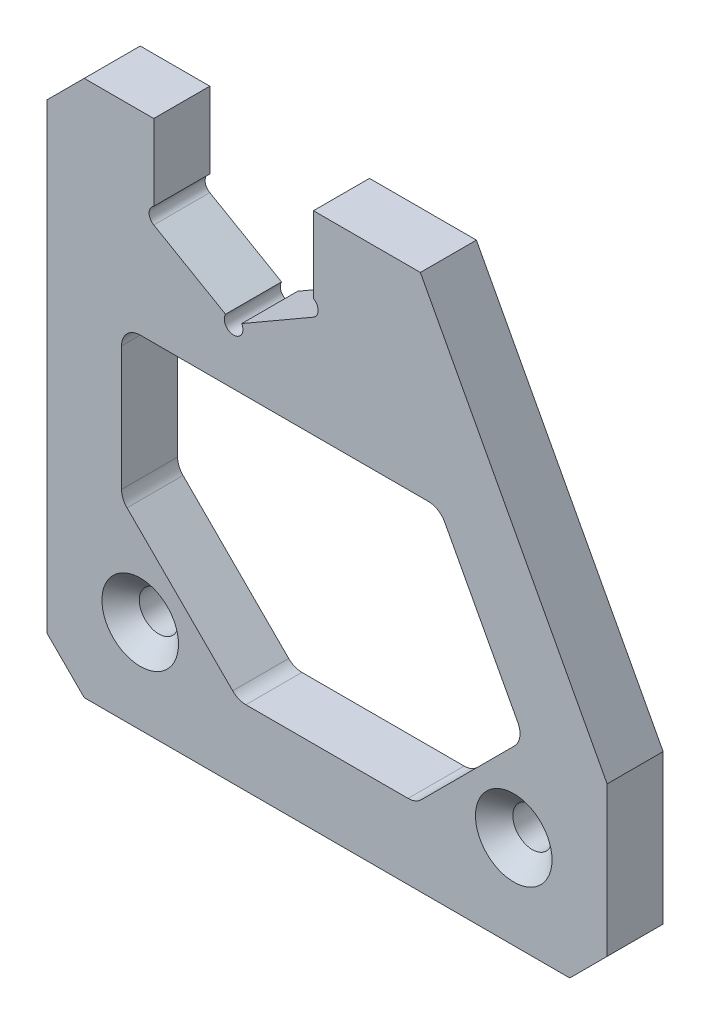
SolidWorks part; units mm, degrees
ref_plane "前视基准面" through (0, 0, 0) normal (0, 0, 1) x (1, 0, 0)
ref_plane "上视基准面" through (0, 0, 0) normal (0, 1, 0) x (1, 0, 0)
ref_plane "右视基准面" through (0, 0, 0) normal (1, 0, 0) x (0, 0, -1)
sketch "草图1" plane through (0, 0, 0) normal (0, 0, 1) x (1, 0, 0)
  line L0 (-20, 4.9363) -> (-20, -52.5)
  line L1 (0, -9.8727) -> (8.55, -4.9363)
  line L2 (8.55, -4.9363) -> (8.55, 4.9363)
  line L3 (8.55, 4.9363) -> (0, 9.8727) construction
  line L4 (0, 9.8727) -> (-8.55, 4.9363) construction
  line L5 (-8.55, 4.9363) -> (-8.55, -4.9363)
  line L6 (-8.55, -4.9363) -> (0, -9.8727)
  line L7 (-20, -52.5) -> (40, -52.5)
  line L8 (-10, -42.5) -> (30, -42.5) construction
  line L11 (40, -32.5) -> (40, -52.5)
  line L13 (20, 4.9363) -> (40, -32.5)
  line L14 (-8.55, 4.9363) -> (-20, 4.9363)
  line L15 (8.55, 4.9363) -> (20, 4.9363)
  circle A0 centre (0, 0) radius 8.55 construction
  circle A1 centre (-10, -42.5) radius 2.1
  circle A2 centre (30, -42.5) radius 2.1
  dimension "D1" = 17.1
  dimension "D4" = 10
  dimension "D6" = 4.2
  dimension "D2" = 20
  dimension "D3" = 52.5
  dimension "D5" = 10
  dimension "D7" = 40
  dimension "D8" = 20
  dimension "D9" = 10
extrude "凸台-拉伸1" add sketch "草图1" along normal mid plane 6
chamfer "倒角1" distance 4 angle 45 3 edges at (40, -52.5, 0) (-20, -52.5, 0) (-20, 4.9363, 0)
sketch "草图2" plane through (0, 0, 3) normal (0, 0, 1) x (1, 0, 0)
  line L0 (0, -9.8727) -> (-8.55, -4.9363) construction
  line L3 (8.55, -4.9363) -> (0, -9.8727) construction
  circle A0 centre (-8.05, -4.0703) radius 1
  circle A1 centre (8.05, -4.0703) radius 1
  circle A2 centre (0, -9.8727) radius 1
  dimension "D1" = 2
extrude "切除-拉伸1" cut sketch "草图2" against normal through all
sketch "草图3" plane through (0, 0, 3) normal (0, 0, 1) x (1, 0, 0)
  line L0 (-12, -15.8727) -> (-12, -32.0147)
  line L1 (-12, -15.8727) -> (22.0469, -15.8727)
  line L2 (22.0469, -15.8727) -> (31.1336, -32.8812)
  line L3 (31.1336, -32.8812) -> (19.5147, -44.5)
  line L4 (19.5147, -44.5) -> (0.4853, -44.5)
  line L5 (0.4853, -44.5) -> (-12, -32.0147)
  line L6 (10, -44.5) -> (10, -52.5) construction
  line L7 (-16, -52.5) -> (36, -52.5) construction
  line L9 (40, -32.5) -> (20, 4.9363) construction
  line L10 (-20, -48.5) -> (-16, -52.5) construction
  line L11 (36, -52.5) -> (40, -48.5) construction
  line L12 (-20, 0.9363) -> (-20, -48.5) construction
  arc A0 (-0.866, -9.3727) -> (0.866, -9.3727) centre (0, -9.8727) ccw construction
  circle A1 centre (-10, -42.5) radius 2.1 construction
  point P21 (-20, -23.7818)
  dimension "D1" = 8
  dimension "D2" = 8
  dimension "D3" = 6
  dimension "D4" = 6
  dimension "D5" = 8
extrude "切除-拉伸2" cut sketch "草图3" against normal through all
fillet "圆角1" radius 2 6 edges at (31.1336, -32.8812, 0) (19.5147, -44.5, 0) (0.4853, -44.5, 0) (-12, -32.0147, 0) (22.0469, -15.8727, 0) (-12, -15.8727, 0)
chamfer "倒角2" distance 2 angle 45 2 edges at (32.1, -42.5, 3) (-7.9, -42.5, 3)
